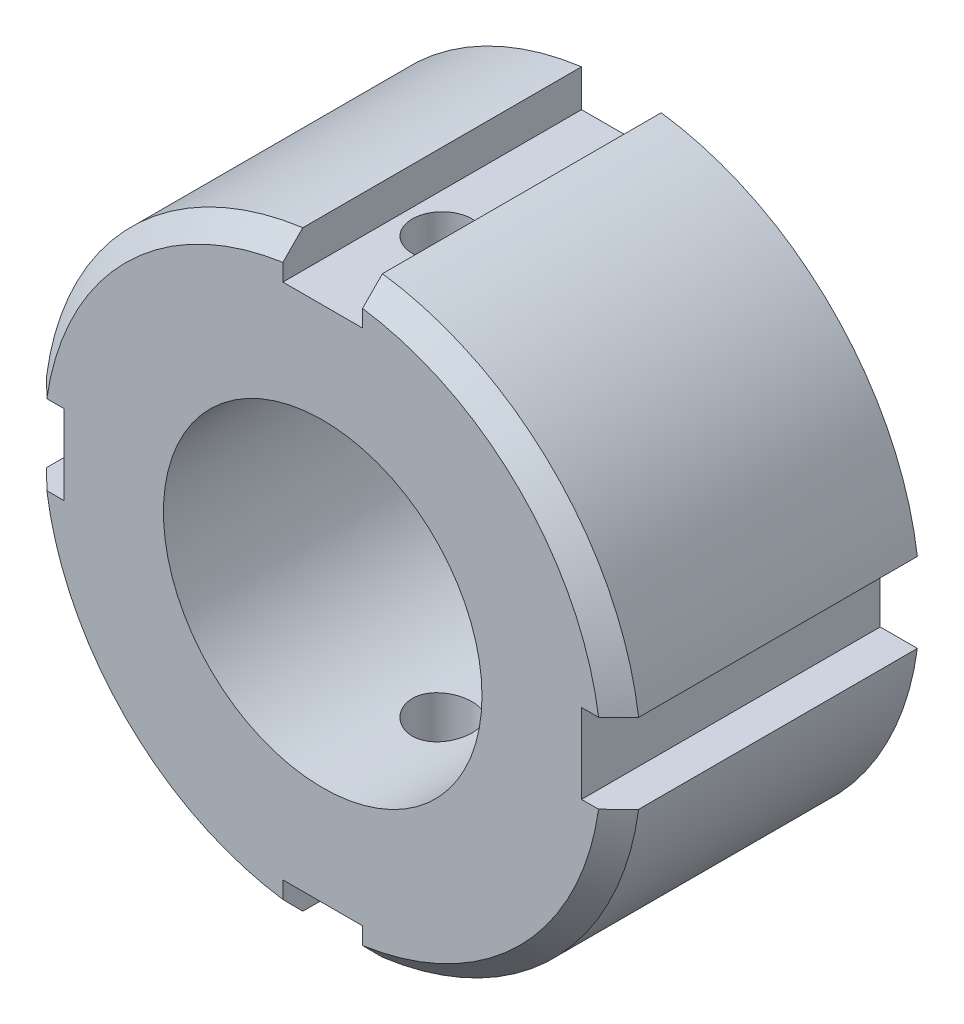
SolidWorks part; units mm, degrees
ref_plane "Front Plane" through (0, 0, 0) normal (0, 0, 1) x (1, 0, 0)
ref_plane "Top Plane" through (0, 0, 0) normal (0, 1, 0) x (1, 0, 0)
ref_plane "Right Plane" through (0, 0, 0) normal (1, 0, 0) x (0, 0, -1)
sketch "Sketch1" plane through (0, 0, 0) normal (0, 0, 1) x (1, 0, 0)
  circle A0 centre (0, 0) radius 15
  dimension "D1" = 30
extrude "Boss-Extrude1" add sketch "Sketch1" along normal mid plane 15
sketch "Sketch2" plane through (0, 0, 7.5) normal (0, 0, 1) x (1, 0, 0)
  circle A0 centre (0, 0) radius 8
  dimension "D1" = 16
extrude "Cut-Extrude1" cut sketch "Sketch2" against normal through all
sketch "Sketch3" plane through (0, 0, 7.5) normal (0, 0, 1) x (1, 0, 0)
  line L0 (0, 19.9054) -> (0, 0)
  line L1 (17, 2) -> (17, -2)
  line L2 (-2, 17) -> (2, 17)
  line L3 (-2, 17) -> (-2, 13)
  line L4 (-2, 13) -> (2, 13)
  line L5 (2, 17) -> (2, 13)
  line L6 (-2, 17) -> (2, 13) construction
  line L7 (-2, 13) -> (2, 17) construction
  line L8 (17, 2) -> (13, 2)
  line L9 (13, 2) -> (13, -2)
  line L10 (17, -2) -> (13, -2)
  line L11 (2, -17) -> (-2, -17)
  line L12 (2, -17) -> (2, -13)
  line L13 (2, -13) -> (-2, -13)
  line L14 (-2, -17) -> (-2, -13)
  line L15 (-17, -2) -> (-17, 2)
  line L16 (-17, -2) -> (-13, -2)
  line L17 (-13, -2) -> (-13, 2)
  line L18 (-17, 2) -> (-13, 2)
  circle A0 centre (0, 0) radius 15 construction
  point P3 (0, 15)
  point P25 (0, 0)
  circle M2 centre (0, 0) radius 15
  dimension "D1" = 4
  dimension "D2" = 2
  dimension "D3" = 4
extrude "Cut-Extrude2" cut sketch "Sketch3" against normal blind 15 contours L3 L4 L0 M2 | L2 L3 L0 M2 | L18 L16 L17 M2 | L18 L15 L16 M2 | L14 L12 L13 M2 | L14 L11 L12 M2 | L10 L8 L9 M2 | L10 L1 L8 M2
chamfer "Chamfer1" distance 1 angle 45 4 edges at (10.6066, 10.6066, 7.5) (10.6066, -10.6066, 7.5) (-10.6066, -10.6066, 7.5) (-10.6066, 10.6066, 7.5)
sketch "Sketch4" plane through (0, -13, 0) normal (0, -1, 0) x (1, 0, 0)
  line L0 (0, 8.2604) -> (0, -9.031) construction
  line L1 (2, 7.5) -> (-2, 7.5) construction
  circle A0 centre (0, 1.5) radius 1.5
  dimension "D1" = 3
  dimension "D2" = 6
extrude "Cut-Extrude3" cut sketch "Sketch4" against normal through all
